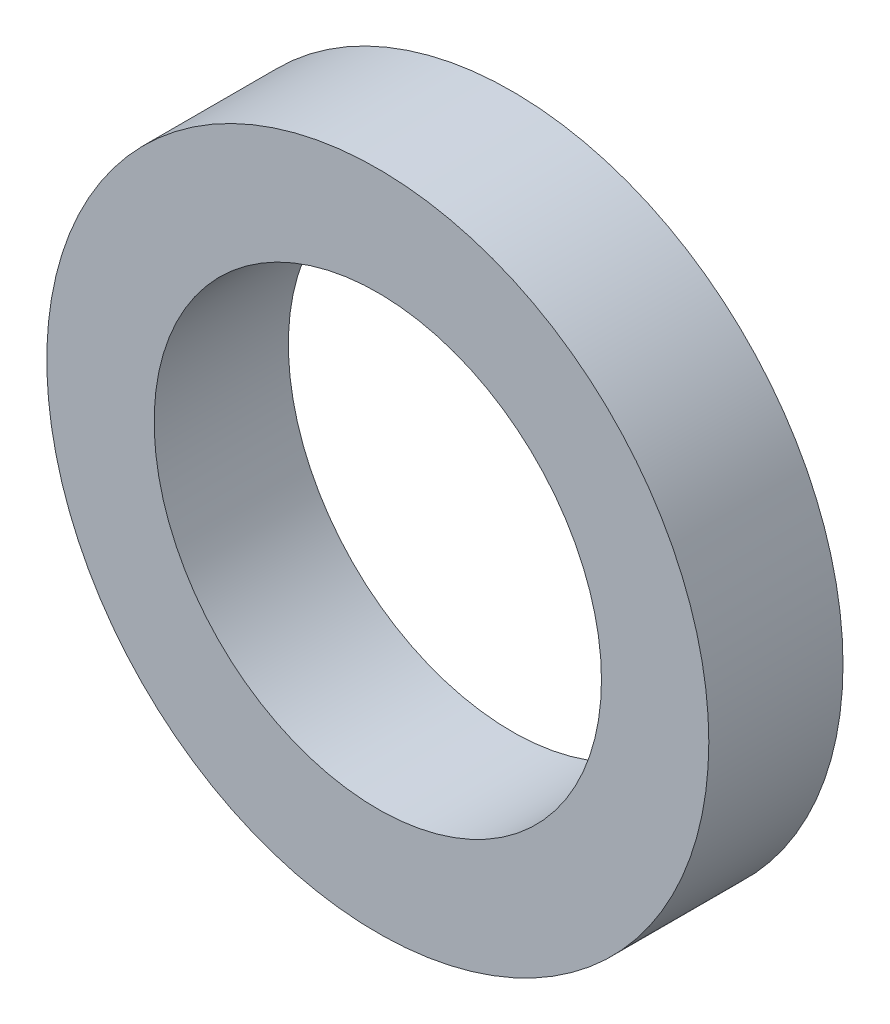
SolidWorks part; units mm, degrees
ref_plane "Front Plane" through (0, 0, 0) normal (0, 0, 1) x (1, 0, 0)
ref_plane "Top Plane" through (0, 0, 0) normal (0, 1, 0) x (1, 0, 0)
ref_plane "Right Plane" through (0, 0, 0) normal (1, 0, 0) x (0, 0, -1)
sketch "Sketch1" plane through (0, 0, 0) normal (0, 0, 1) x (1, 0, 0)
  circle A0 centre (0, 0) radius 3.7
  circle A1 centre (0, 0) radius 2.5
  dimension "D1" = 7.4
  dimension "D2" = 5
extrude "Boss-Extrude1" add sketch "Sketch1" along normal blind 1.5
